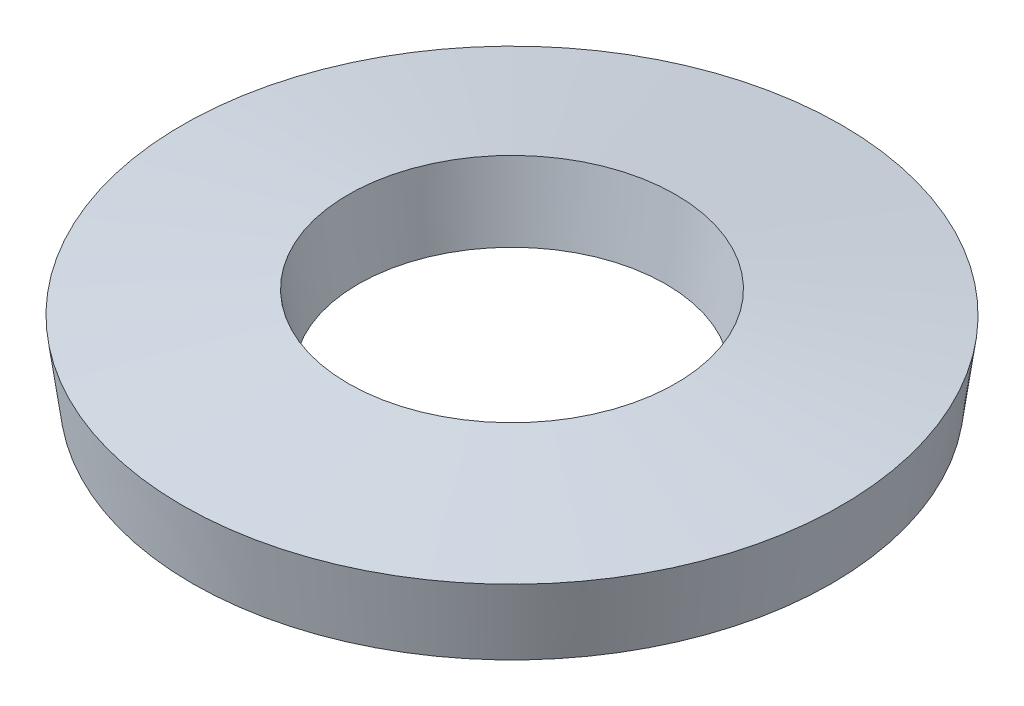
SolidWorks part; units mm, degrees
ref_plane "Front" through (0, 0, 0) normal (0, 0, 1) x (1, 0, 0)
ref_plane "Top" through (0, 0, 0) normal (0, 1, 0) x (1, 0, 0)
ref_plane "Right" through (0, 0, 0) normal (1, 0, 0) x (0, 0, -1)
sketch "Sketch1" plane through (0, 0, 0) normal (0, 0, 1) x (1, 0, 0)
  line L0 (8.7295, 0) -> (4.2, 0.6184)
  line L1 (4.2, 0.6184) -> (4.4705, 2.6)
  line L2 (4.4705, 2.6) -> (9, 1.9816)
  line L3 (9, 1.9816) -> (8.7295, 0)
  line L4 (0, 0) -> (0, 2.6) construction
  point P5 (4.3353, 1.6092)
  dimension "D1" = 4.5715
  dimension "ID" = 8.4
  dimension "OD" = 18
  dimension "Thickness" = 2
  dimension "Height" = 2.6
revolve "Revolve1" add sketch "Sketch1" angle 360 about L4
sketch "Sketch15" plane through (0, 0, 0) normal (0, 1, 0) x (1, 0, 0)
  circle A0 centre (0, 0) radius 9
  circle A1 centre (0, 0) radius 4.2
